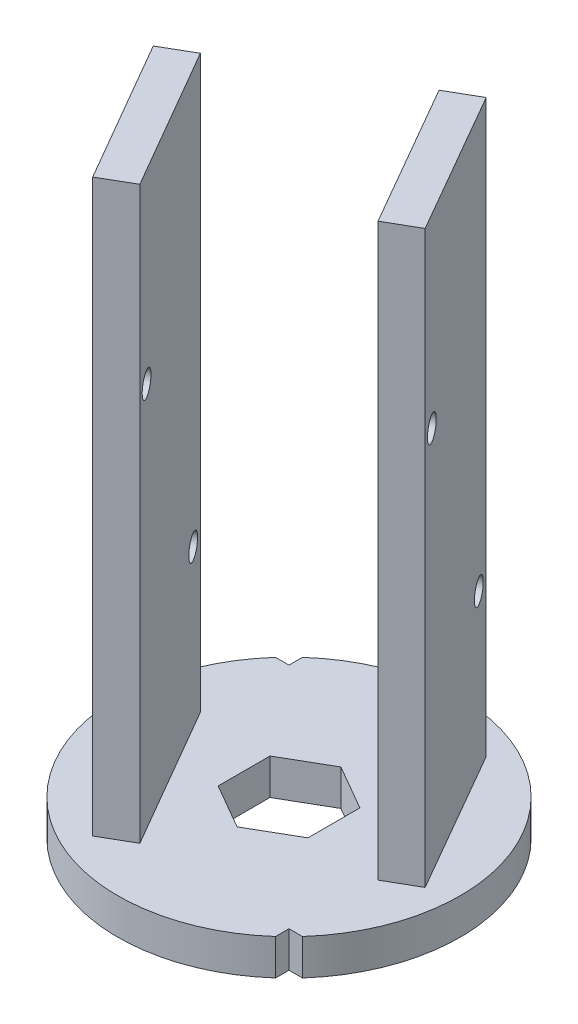
SolidWorks part; units mm, degrees
ref_plane "Front Plane" through (0, 0, 0) normal (0, 0, 1) x (1, 0, 0)
ref_plane "Top Plane" through (0, 0, 0) normal (0, 1, 0) x (1, 0, 0)
ref_plane "Right Plane" through (0, 0, 0) normal (1, 0, 0) x (0, 0, -1)
sketch "Sketch2" plane through (0, 0, 0) normal (0, 1, 0) x (1, 0, 0)
  line L0 (0, 0) -> (0, 38.1) construction
  line L1 (0, 11.547) -> (-10, 5.7735)
  line L2 (-10, 5.7735) -> (-10, -5.7735)
  line L3 (-10, -5.7735) -> (0, -11.547)
  line L4 (0, -11.547) -> (10, -5.7735)
  line L5 (10, -5.7735) -> (10, 5.7735)
  line L6 (10, 5.7735) -> (0, 11.547)
  line L7 (0, 0) -> (-38.1, 0) construction
  line L8 (0, 0) -> (38.1, 0) construction
  line L9 (0, 0) -> (0, -38.1) construction
  line L11 (-38.1, 0) -> (-25.4, 0)
  line L12 (-38.1, 0) -> (-38.1, 31.75)
  line L13 (-38.1, 31.75) -> (-25.4, 31.75)
  line L14 (-25.4, 0) -> (-25.4, 31.75)
  line L15 (0, 38.1) -> (-31.75, 38.1)
  line L16 (0, 38.1) -> (0, 25.4)
  line L17 (0, 25.4) -> (-31.75, 25.4)
  line L18 (-31.75, 38.1) -> (-31.75, 25.4)
  line L19 (38.1, 0) -> (25.4, 0)
  line L20 (38.1, 0) -> (38.1, -31.75)
  line L21 (38.1, -31.75) -> (25.4, -31.75)
  line L22 (25.4, 0) -> (25.4, -31.75)
  line L23 (0, -38.1) -> (31.75, -38.1)
  line L24 (0, -38.1) -> (0, -25.4)
  line L25 (0, -25.4) -> (31.75, -25.4)
  line L26 (31.75, -38.1) -> (31.75, -25.4)
  circle A0 centre (0, 0) radius 38.1
  circle A1 centre (0, 0) radius 10 construction
  dimension "D1" = 76.2
  dimension "D2" = 20
  dimension "D3" = 12.7
  dimension "D4" = 31.75
  dimension "D5" = 31.75
  dimension "D6" = 12.7
  dimension "D7" = 12.7
  dimension "D8" = 31.75
  dimension "D9" = 31.75
  dimension "D10" = 12.7
extrude "Boss-Extrude1" add sketch "Sketch2" along normal blind 8 contours L13 A0 L11 L14 | L16 A0 L18 L17 | L21 A0 L19 L22 | L24 A0 L26 L25 | L26 A0 L21 L22 L19 L16 L17 L18 L13 L14 L11 L24 L25 L6 L5 L4 L3 L2 L1
sketch "Sketch7" plane through (0, 8, 0) normal (0, 1, 0) x (1, 0, 0)
  line L0 (-20.2575, 7.7057) -> (-32.8247, 2.6102) construction
  line L1 (1.6846, 20.374) -> (-24.8988, 5.026) construction
  line L2 (-2.5209, -22.5726) -> (-14.3077, -29.3777) construction
  line L3 (-6.6939, -24.9819) -> (24.9819, -6.6939) construction
  line L4 (-32.8247, 2.6102) -> (-14.3077, -29.3777)
  line L5 (-32.8247, 2.6102) -> (-26.1763, 6.4588)
  line L6 (-14.3077, -29.3777) -> (-7.6593, -25.5291)
  line L7 (-26.1763, 6.4588) -> (-7.6593, -25.5291)
  point P8 (-20.2575, 7.7057)
extrude "Boss-Extrude3" add sketch "Sketch7" along normal blind 127
ref_plane "Plane1" through (-21.7457, -1.979, -37.6647) normal (0.866, 0, -0.5) x (-0.5, 0, -0.866)
mirror "Mirror1" about plane through (-21.7457, -1.979, -37.6647) normal (0.866, 0, -0.5) of "Boss-Extrude3"
sketch "Sketch8" plane through (23.4853, 0, -13.5234) normal (0.8666, 0, -0.499) x (-0.499, 0, -0.8666)
  line L0 (18.3098, 8.762) -> (-18.3098, 8.762) construction
  circle A0 centre (-14.2022, 93.725) radius 2.667
  circle A1 centre (14.2458, 42.925) radius 2.667
  dimension "D1" = 5.334
  dimension "D2" = 5.334
extrude "Cut-Extrude1" cut sketch "Sketch8" against normal blind 127
